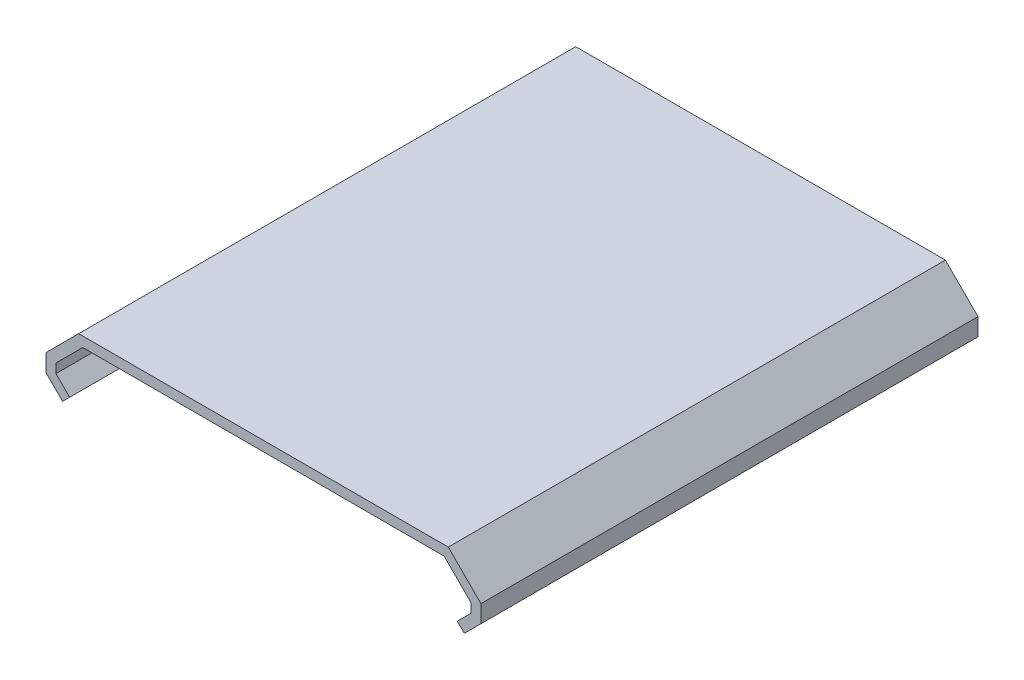
SolidWorks part; units mm, degrees
ref_plane "前视基准面" through (0, 0, 0) normal (0, 0, 1) x (1, 0, 0)
ref_plane "上视基准面" through (0, 0, 0) normal (0, 1, 0) x (1, 0, 0)
ref_plane "右视基准面" through (0, 0, 0) normal (1, 0, 0) x (0, 0, -1)
sketch "草图1" plane through (0, 0, 0) normal (0, 0, 1) x (1, 0, 0)
  line L0 (0, 0.9142) -> (0, 50.6932) construction
  line L1 (83.5, 40.279) -> (78, 34.779)
  line L2 (72.7071, 54.779) -> (-72.7071, 54.779)
  line L3 (-72.7071, 54.779) -> (-83.5, 43.9861)
  line L4 (-83.5, 43.9861) -> (-83.5, 40.279)
  line L5 (-83.5, 40.279) -> (-78, 34.779)
  line L6 (-77, 33.779) -> (-83, 39.779) construction
  line L7 (83.5, 43.9861) -> (83.5, 40.279)
  line L8 (-83, 43.779) -> (-77, 49.779) construction
  line L9 (-83, 39.779) -> (-83, 43.779) construction
  line L10 (-77, 49.779) -> (-74, 49.779) construction
  line L11 (-77, 0) -> (-77, 33.779) construction
  line L12 (72.7071, 54.779) -> (83.5, 43.9861)
  point P22 (0, 54.779)
  dimension "D1" = 0.5
  dimension "D2" = 0.5
  dimension "D3" = 5
  dimension "D4" = 1
extrude "拉伸-薄壁1" add sketch "草图1" against normal blind 200 thin thin type one direction reverse wall 4
